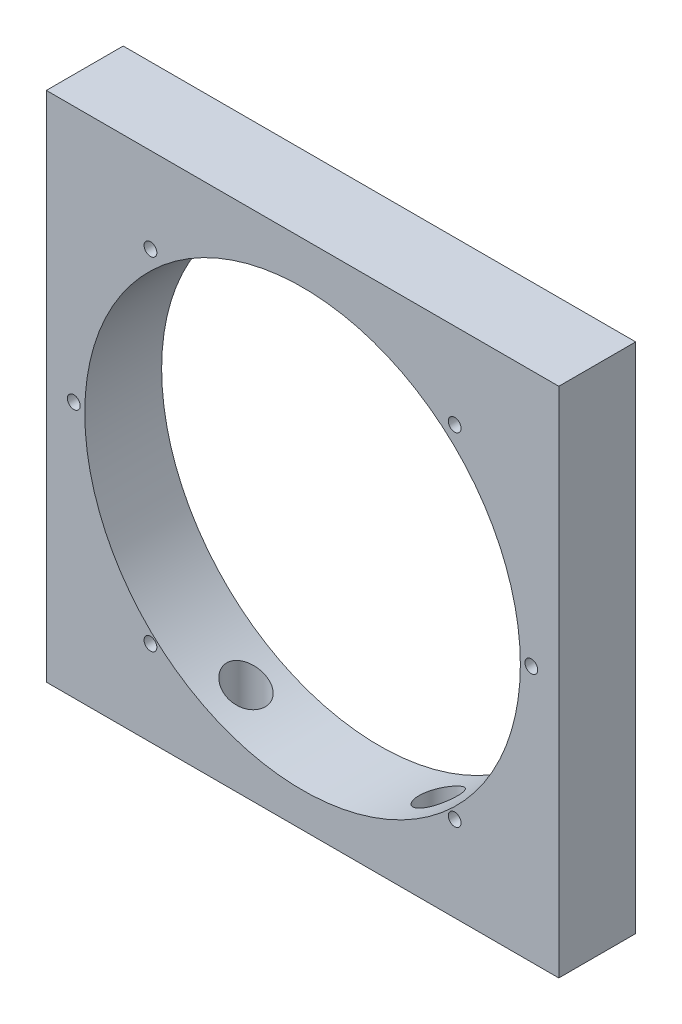
SolidWorks part; units mm, degrees
ref_plane "Front Plane" through (0, 0, 0) normal (0, 0, 1) x (1, 0, 0)
ref_plane "Top Plane" through (0, 0, 0) normal (0, 1, 0) x (1, 0, 0)
ref_plane "Right Plane" through (0, 0, 0) normal (1, 0, 0) x (0, 0, -1)
sketch "Sketch1" plane through (0, 0, 0) normal (0, 0, 1) x (1, 0, 0)
  line L0 (0, 28.3212) -> (0, -11.6788) construction
  line L1 (-20, 28.3212) -> (20, 28.3212)
  line L2 (20, 28.3212) -> (20, -11.6788)
  line L3 (20, -11.6788) -> (-20, -11.6788)
  line L4 (-20, 28.3212) -> (-20, -11.6788)
  line L5 (-20, 8.3212) -> (20, 8.3212) construction
  circle A0 centre (0, 8.3212) radius 18
  circle A1 centre (12.7279, 21.0491) radius 0.5
  circle A2 centre (12.7279, -4.4067) radius 0.5
  circle A3 centre (18, 8.3212) radius 0.5
  circle A4 centre (-12.7279, -4.4067) radius 0.5
  circle A5 centre (-18, 8.3212) radius 0.5
  circle A6 centre (-12.7279, 21.0491) radius 0.5
  point P23 (0, 0)
  point P24 (0, 0)
  dimension "D3" = 36
  dimension "D1" = 40
  dimension "D2" = 40
extrude "Boss-Extrude1" add sketch "Sketch1" along normal mid plane 6 contours L3 L4 L1 L2
sketch "Sketch3" plane through (0, 0, 3) normal (0, 0, 1) x (1, 0, 0)
  line L0 (0, -11.6788) -> (0, 28.9263) construction
  line L1 (20, -11.6788) -> (-20, -11.6788) construction
  line L2 (-20, 8.3212) -> (20, 8.3212) construction
  line L3 (-20, 28.3212) -> (-20, -11.6788) construction
  line L4 (20, 28.3212) -> (20, -11.6788) construction
  line L5 (11.8722, -5.0169) -> (-11.8722, 21.6593) construction
  line L6 (11.8722, 21.6593) -> (-11.8722, -5.0169) construction
  circle A1 centre (-11.8722, 21.6593) radius 0.5
  circle A2 centre (-17.8565, 8.3212) radius 0.5
  circle A3 centre (-11.8722, -5.0169) radius 0.5
  circle A4 centre (11.8722, -5.0169) radius 0.5
  circle A5 centre (17.8565, 8.3212) radius 0.5
  circle A6 centre (11.8722, 21.6593) radius 0.5
  point P27 (0, 0)
extrude "Cut-Extrude1" cut sketch "Sketch3" against normal blind 40
sketch "Sketch4" plane through (0, 0, 0) normal (0, 1, 0) x (1, 0, 0)
  line L0 (-20, 0) -> (20, 0) construction
  line L1 (-20, -3) -> (-20, 3) construction
  line L2 (20, -3) -> (20, 3) construction
  line L3 (0, 3) -> (0, -3) construction
  line L4 (-20, 3) -> (20, 3) construction
  line L5 (-20, -3) -> (20, -3) construction
  line L6 (-7.5, 1.5326) -> (-7.5, -1.3623) construction
  line L7 (7.5, 1.5326) -> (7.5, -1.3623) construction
  circle A0 centre (-7.5, 0.0851) radius 1.5
  circle A1 centre (7.5, 0.0851) radius 1.5
  dimension "D1" = 15
extrude "Cut-Extrude3" cut sketch "Sketch4" against normal blind 30
sketch "Sketch5" plane through (0, 0, 3) normal (0, 0, 1) x (1, 0, 0)
  circle A0 centre (0, 8.0121) radius 17
  point P2 (0, 0)
extrude "Cut-Extrude7" cut sketch "Sketch5" against normal through all
